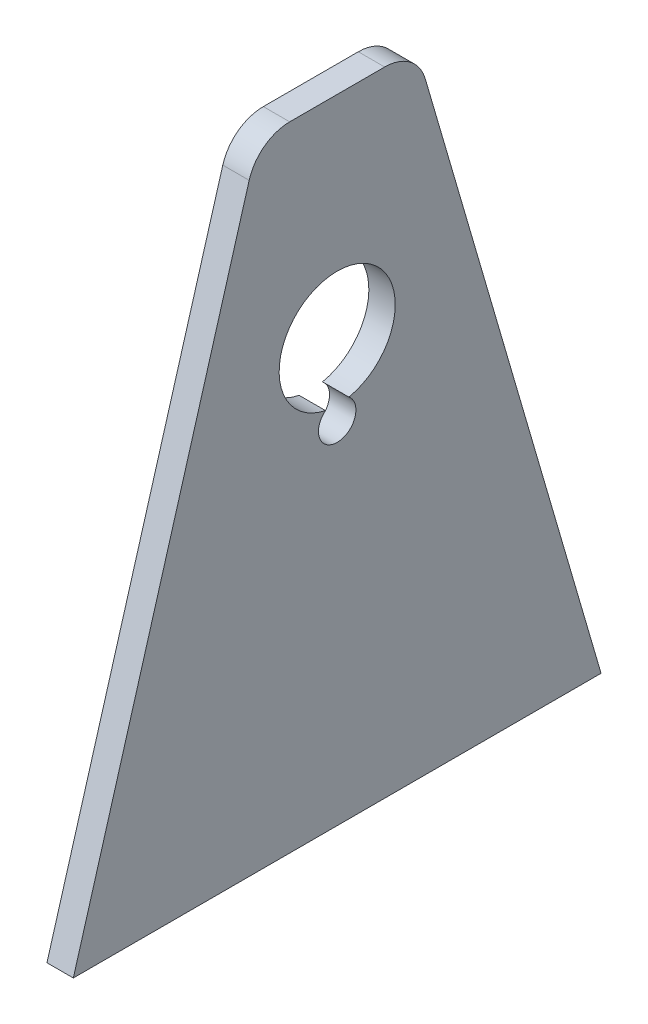
SolidWorks part; units mm, degrees
ref_plane "Front Plane" through (0, 0, 0) normal (0, 0, 1) x (1, 0, 0)
ref_plane "Top Plane" through (0, 0, 0) normal (0, 1, 0) x (1, 0, 0)
ref_plane "Right Plane" through (0, 0, 0) normal (1, 0, 0) x (0, 0, -1)
sketch "Sketch1" plane through (0, 0, 0) normal (1, 0, 0) x (0, 0, -1)
  line L0 (0, 0) -> (0, -17.2085) construction
  line L5 (9.8783, -9.8783) -> (-9.8783, 9.8783) construction
  line L6 (9.8783, 9.8783) -> (-9.8783, -9.8783) construction
  line L7 (-63.5, -101.6) -> (-19.05, 50.8)
  line L8 (-19.05, 50.8) -> (19.05, 50.8)
  line L9 (19.05, 50.8) -> (63.5, -101.6)
  line L10 (63.5, -101.6) -> (-63.5, -101.6)
  line L11 (0, 50.8) -> (0, -101.6) construction
  arc A0 (2.8117, -13.6841) -> (-2.8117, -13.6841) centre (0, 0) ccw
  circle A1 centre (0, -17.2085) radius 3.2385 construction
  arc A2 (2.8117, -13.6841) -> (-2.8117, -13.6841) centre (0, -17.2085) cw
  point P0 (0, 0)
  point P17 (31.2425, -89.5841)
  point P18 (0, 0)
  point P19 (0, 0)
  point P20 (0, 0)
  dimension "D3" = 27.94
  dimension "D4" = 6.477
  dimension "D5" = 1.27
  dimension "D1" = 152.4
  dimension "D2" = 101.6
  dimension "D6" = 127
  dimension "D7" = 38.1
extrude "Boss-Extrude1" add sketch "Sketch1" along normal blind 6.35
fillet "Fillet2" radius 10.16 2 edges at (3.175, 50.8, -19.05) (3.175, 50.8, 19.05)
